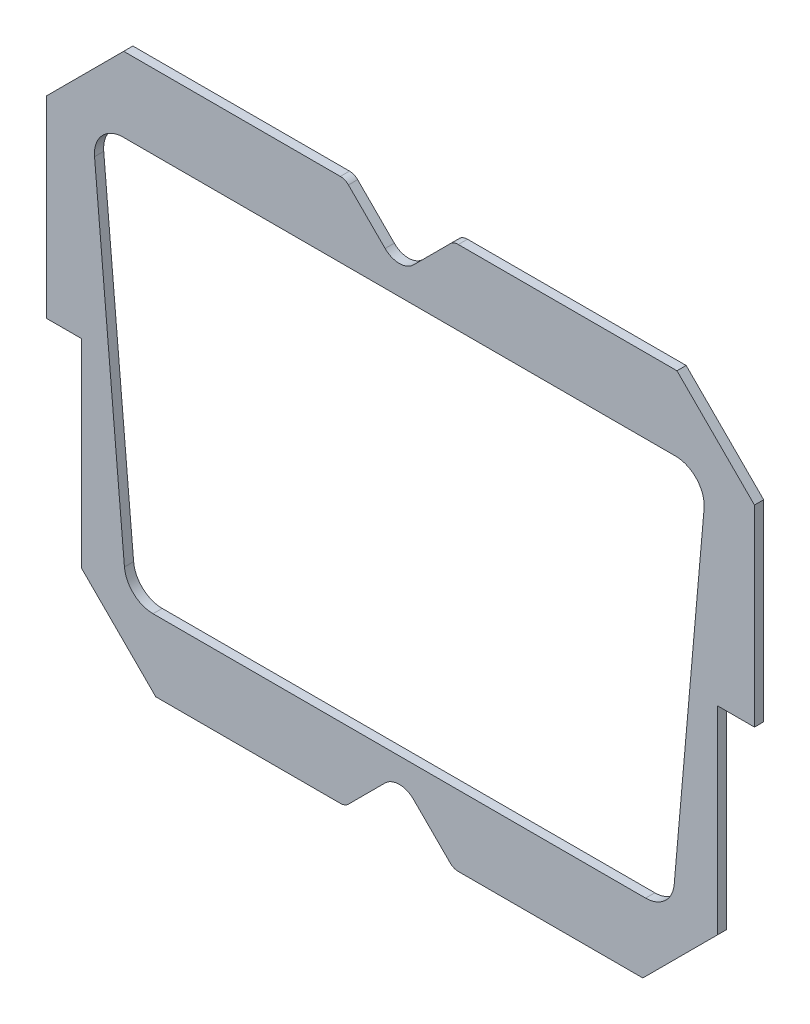
SolidWorks part; units mm, degrees
ref_plane "Plan de face" through (0, 0, 0) normal (0, 0, 1) x (1, 0, 0)
ref_plane "Plan de dessus" through (0, 0, 0) normal (0, 1, 0) x (1, 0, 0)
ref_plane "Plan de droite" through (0, 0, 0) normal (1, 0, 0) x (0, 0, -1)
sketch "Esquisse1" plane through (0, 0, 0) normal (0, 0, 1) x (1, 0, 0)
  line L0 (-48.0234, 96.3492) -> (-10.2782, 96.3492)
  line L1 (-42.4286, 1.7492) -> (-10.2782, 1.7492)
  line L2 (-48.0234, 96.3492) -> (-61.5, 82.8726)
  line L3 (48.3699, 96.3492) -> (61.8799, 82.8393)
  line L4 (61.8799, 82.8393) -> (61.8799, 49.3284)
  line L5 (61.8799, 49.3284) -> (55.4, 49.3284)
  line L6 (55.4, 49.3284) -> (55.4, 14.7275)
  line L7 (55.4, 14.7275) -> (42.4217, 1.7492)
  line L8 (-61.5, 49.3284) -> (-55.4, 49.3284)
  line L9 (-42.4286, 1.7492) -> (-55.4, 14.7206)
  line L10 (-55.4, 14.7206) -> (-55.4, 49.3284)
  line L11 (-8.864, 2.335) -> (-2.4749, 8.7241)
  line L12 (10.2782, 1.7492) -> (42.4217, 1.7492)
  line L13 (-61.5, 49.3284) -> (-61.5, 82.8726)
  line L14 (-50.6521, 97.8492) -> (50.6521, 97.8492) construction
  line L15 (8.864, 2.335) -> (2.4749, 8.7241)
  line L16 (-63, 47.1492) -> (-63, 88.2492) construction
  line L17 (-57, 38.2492) -> (-57, 3.2492) construction
  line L18 (57, 3.2492) -> (57, 38.2492) construction
  line L19 (-8.864, 95.7634) -> (-2.4749, 89.3743)
  line L20 (56.1716, 84.8492) -> (-56.1716, 84.8492) construction
  line L21 (-48.1185, 83.3492) -> (48.1185, 83.3492)
  line L22 (53.0994, 77.9117) -> (47.8913, 18.6117)
  line L23 (42.9105, 14.0492) -> (-42.9105, 14.0492)
  line L24 (-47.8913, 18.6117) -> (-53.0994, 77.9117)
  line L25 (0, 100.8447) -> (0, -4.5731) construction
  line L26 (8.864, 95.7634) -> (2.4749, 89.3743)
  line L27 (10.2782, 96.3492) -> (48.3699, 96.3492)
  arc A0 (53.0994, 77.9117) -> (48.1185, 83.3492) centre (48.1185, 78.3492) ccw
  arc A1 (-53.0994, 77.9117) -> (-48.1185, 83.3492) centre (-48.1185, 78.3492) cw
  arc A2 (-42.9105, 14.0492) -> (-47.8913, 18.6117) centre (-42.9105, 19.0492) cw
  arc A3 (42.9105, 14.0492) -> (47.8913, 18.6117) centre (42.9105, 19.0492) ccw
  arc A4 (-2.4749, 8.7241) -> (2.4749, 8.7241) centre (0, 6.2492) cw
  arc A5 (-10.2782, 1.7492) -> (-8.864, 2.335) centre (-10.2782, 3.7492) ccw
  arc A6 (10.2782, 1.7492) -> (8.864, 2.335) centre (10.2782, 3.7492) cw
  arc A7 (-2.4749, 89.3743) -> (2.4749, 89.3743) centre (0, 91.8492) ccw
  arc A8 (-8.864, 95.7634) -> (-10.2782, 96.3492) centre (-10.2782, 94.3492) ccw
  arc A9 (10.2782, 96.3492) -> (8.864, 95.7634) centre (10.2782, 94.3492) ccw
  point P55 (-9.4497, 96.3492)
  point P58 (9.4497, 96.3492)
  dimension "D11" = 5
  dimension "D12" = 5
  dimension "D2" = 3.5
  dimension "D14" = 2
  dimension "D16" = 3.5
  dimension "D18" = 2
  dimension "D1" = 1.5
  dimension "D3" = 1.5
  dimension "D4" = 1.6
  dimension "D5" = 1.6
  dimension "D6" = 4.5
  dimension "D7" = 45
  dimension "D8" = 1.5
  dimension "D9" = 1.5
  dimension "D10" = 1.5
  dimension "D13" = 45
  dimension "D15" = 45
  dimension "D17" = 4.5
extrude "Extrusion1" add sketch "Esquisse1" along normal blind 1.6
